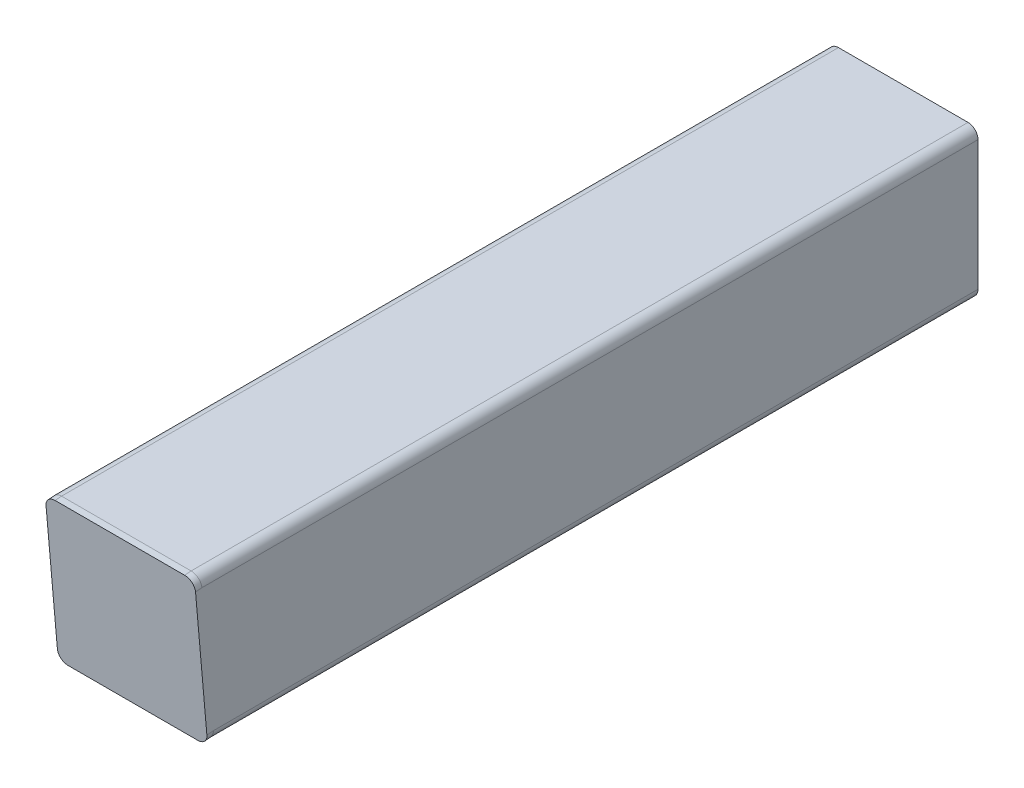
SolidWorks part; units mm, degrees
material "ASTM A500 Grade B Steel"
ref_plane "Front Plane" through (0, 0, 0) normal (0, 0, 1) x (1, 0, 0)
ref_plane "Top Plane" through (0, 0, 0) normal (0, 1, 0) x (1, 0, 0)
ref_plane "Right Plane" through (0, 0, 0) normal (1, 0, 0) x (0, 0, -1)
sketch "Sketch1" plane through (0, 0, 0) normal (0, 0, 1) x (1, 0, 0)
  line L0 (5.3086, -2.7686) -> (32.7914, -2.7686)
  line L1 (2.54, 0) -> (35.56, 0)
  line L2 (0, -2.54) -> (0, -35.56)
  line L3 (2.54, -38.1) -> (35.56, -38.1)
  line L4 (38.1, -2.54) -> (38.1, -35.56)
  line L5 (35.3314, -5.3086) -> (35.3314, -32.7914)
  line L6 (5.3086, -35.3314) -> (32.7914, -35.3314)
  line L7 (2.7686, -5.3086) -> (2.7686, -32.7914)
  line L8 (0, 0) -> (0, -38.1) construction
  line L9 (0, -38.1) -> (38.1, -38.1) construction
  line L10 (38.1, 0) -> (38.1, -38.1) construction
  line L11 (2.7686, -2.7686) -> (2.7686, -35.3314) construction
  line L12 (2.7686, -35.3314) -> (35.3314, -35.3314) construction
  line L13 (35.3314, -2.7686) -> (35.3314, -35.3314) construction
  line L14 (2.7686, -2.7686) -> (35.3314, -2.7686) construction
  line L15 (0, 0) -> (38.1, 0) construction
  arc A0 (0, -35.56) -> (2.54, -38.1) centre (2.54, -35.56) ccw
  arc A1 (38.1, -35.56) -> (35.56, -38.1) centre (35.56, -35.56) cw
  arc A2 (2.7686, -32.7914) -> (5.3086, -35.3314) centre (5.3086, -32.7914) ccw
  arc A3 (32.7914, -35.3314) -> (35.3314, -32.7914) centre (32.7914, -32.7914) ccw
  arc A4 (35.3314, -5.3086) -> (32.7914, -2.7686) centre (32.7914, -5.3086) ccw
  arc A5 (38.1, -2.54) -> (35.56, 0) centre (35.56, -2.54) ccw
  arc A6 (0, -2.54) -> (2.54, 0) centre (2.54, -2.54) cw
  arc A7 (5.3086, -2.7686) -> (2.7686, -5.3086) centre (5.3086, -5.3086) ccw
  point P12 (0, -38.1)
  dimension "D4" = 2.54
  dimension "D3" = 2.7686
extrude "Boss-Extrude1" add sketch "Sketch1" along normal blind 198
sketch "Sketch3" plane through (38.1, 0, 0) normal (1, 0, 0) x (0, 0, -1)
  line L0 (-198, 0) -> (-194.6667, -38.1)
  line L1 (-198, -38.1) -> (0, -38.1) construction
  line L2 (-194.6667, -38.1) -> (-198, -38.1)
  line L3 (-198, -38.1) -> (-198, 0)
  dimension "D1" = 5
extrude "Cut-Extrude3" cut sketch "Sketch3" against normal through all
sketch "Sketch4" plane through (0, -17.1912, 196.496) normal (0, -0.0872, 0.9962) x (1, 0, 0)
  line L4 (2.54, -20.9887) -> (35.56, -20.9887)
  line L5 (38.1, -18.439) -> (38.1, 14.7071)
  line L6 (35.56, 17.2568) -> (2.54, 17.2568)
  line L7 (0, 14.7071) -> (0, -18.439)
  line L8 (2.54, -20.9887) -> (35.56, -20.9887)
  line L9 (38.1, -18.439) -> (38.1, 14.7071)
  line L10 (35.56, 17.2568) -> (2.54, 17.2568)
  line L11 (0, 14.7071) -> (0, -18.439)
  ellipse E4 centre (35.56, -18.439) end of major axis (35.56, -20.9887) minor radius 2.54 (35.56, -20.9887) -> (38.1, -18.439) ccw
  ellipse E5 centre (35.56, 14.7071) end of major axis (35.56, 17.2568) minor radius 2.54 (38.1, 14.7071) -> (35.56, 17.2568) ccw
  ellipse E6 centre (2.54, 14.7071) end of major axis (2.54, 12.1574) minor radius 2.54 (2.54, 17.2568) -> (0, 14.7071) ccw
  ellipse E7 centre (2.54, -18.439) end of major axis (2.54, -20.9887) minor radius 2.54 (0, -18.439) -> (2.54, -20.9887) ccw
  ellipse E8 centre (35.56, -18.439) end of major axis (35.56, -20.9887) minor radius 2.54 (35.56, -20.9887) -> (38.1, -18.439) ccw
  ellipse E9 centre (35.56, 14.7071) end of major axis (35.56, 17.2568) minor radius 2.54 (38.1, 14.7071) -> (35.56, 17.2568) ccw
  ellipse E10 centre (2.54, 14.7071) end of major axis (2.54, 12.1574) minor radius 2.54 (2.54, 17.2568) -> (0, 14.7071) ccw
  ellipse E11 centre (2.54, -18.439) end of major axis (2.54, -20.9887) minor radius 2.54 (0, -18.439) -> (2.54, -20.9887) ccw
  dimension "D1" = 0
extrude "Boss-Extrude2" add sketch "Sketch4" along normal up to surface (1.6363 mm away)
